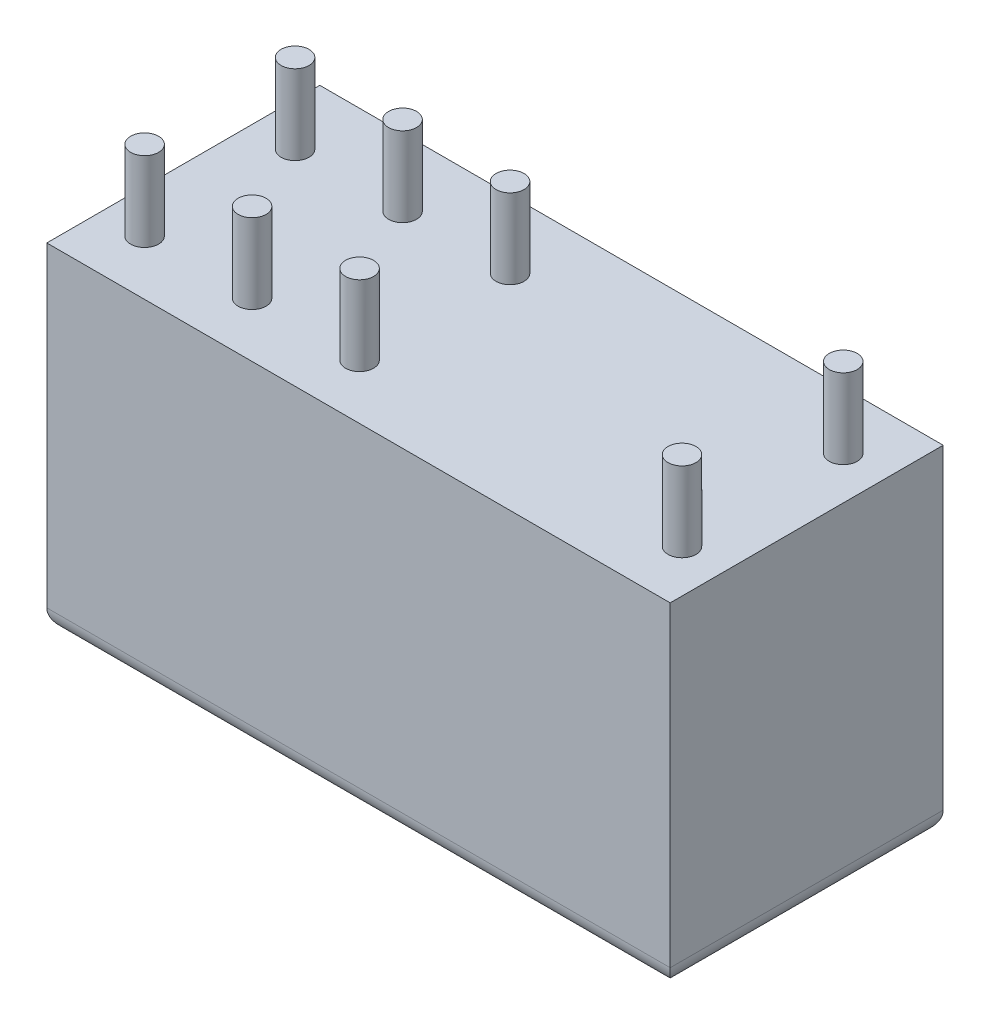
SolidWorks part; units mm, degrees
ref_plane "Front Plane" through (0, 0, 0) normal (0, 0, 1) x (1, 0, 0)
ref_plane "Top Plane" through (0, 0, 0) normal (0, 1, 0) x (1, 0, 0)
ref_plane "Right Plane" through (0, 0, 0) normal (1, 0, 0) x (0, 0, -1)
sketch "Sketch1" plane through (0, 0, 0) normal (0, 1, 0) x (1, 0, 0)
  line L1 (-14.5, -6.35) -> (14.5, -6.35)
  line L2 (-14.5, -6.35) -> (-14.5, 6.35)
  line L3 (-14.5, 6.35) -> (14.5, 6.35)
  line L4 (14.5, -6.35) -> (14.5, 6.35)
  line L5 (-14.5, -6.35) -> (14.5, 6.35) construction
  line L6 (-14.5, 6.35) -> (14.5, -6.35) construction
  point P0 (0, 0)
  dimension "D1" = 29
  dimension "D2" = 12.7
extrude "Boss-Extrude1" add sketch "Sketch1" along normal blind 15.7
sketch "Sketch2" plane through (0, 15.7, 0) normal (0, 1, 0) x (1, 0, 0)
  line L2 (14.5, 0) -> (-14.5, 0) construction
  line L3 (14.5, -6.35) -> (14.5, 6.35) construction
  line L4 (-14.5, 6.35) -> (-14.5, -6.35) construction
  line L5 (0, 0) -> (0, -13.7873) construction
  circle A0 centre (12.5, -3.8) radius 0.65
  circle A1 centre (-12.5, -3.8) radius 0.65
  circle A4 centre (-7.5, 3.2) radius 0.65
  circle A5 centre (-2.5, -3.8) radius 0.65
  circle A7 centre (12.5, 3.7) radius 0.65
  circle A8 centre (-2.5, 3.2) radius 0.65
  circle A9 centre (-7.5, -3.8) radius 0.65
  circle A10 centre (-12.5, 3.2) radius 0.65
  dimension "D1" = 1.3
  dimension "D2" = 7.6
  dimension "D3" = 1.3
  dimension "D6" = 7.6
  dimension "D9" = 15
  dimension "D10" = 25
  dimension "D4" = 1
  dimension "D5" = 2
  dimension "D7" = 3
  dimension "D8" = 2
extrude "Boss-Extrude2" add sketch "Sketch2" along normal blind 3.7
fillet "Fillet1" radius 1 4 edges at (14.5, 0, 0) (0, 0, -6.35) (-14.5, 0, 0) (0, 0, 6.35)
